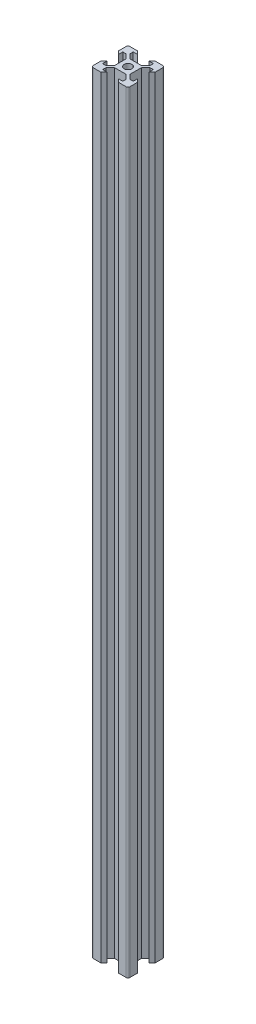
SolidWorks part; units mm, degrees
material "1060 Alloy"
ref_plane "Front Plane" through (0, 0, 0) normal (0, 0, 1) x (1, 0, 0)
ref_plane "Top Plane" through (0, 0, 0) normal (0, 1, 0) x (1, 0, 0)
ref_plane "Right Plane" through (0, 0, 0) normal (1, 0, 0) x (0, 0, -1)
ref_plane "End Plane" through (0, 420, 0) normal (0, 1, 0) x (1, 0, 0)
sketch "MasterLayoutSketch" plane through (0, 0, 0) normal (0, 1, 0) x (1, 0, 0)
  line L0 (-8.325, 3.1) -> (-8.325, 5.5)
  line L1 (-10, -10) -> (10, -10) construction
  line L2 (-10, -10) -> (-10, 10) construction
  line L3 (-10, 10) -> (10, 10) construction
  line L4 (10, -10) -> (10, 10) construction
  line L5 (-10, -10) -> (10, 10) construction
  line L6 (-10, 10) -> (10, -10) construction
  line L7 (-4.775, 10) -> (-3.1, 8.325)
  line L10 (-8.325, 5.5) -> (-6.5607, 5.5)
  line L11 (-10, 4.775) -> (-8.325, 3.1)
  line L12 (-5.5, 8.325) -> (-5.5, 6.5607)
  line L13 (-3.1, 8.325) -> (-5.5, 8.325)
  line L14 (-10, 10) -> (-10, 4.775)
  line L19 (3.1, 8.325) -> (5.5, 8.325)
  line L20 (10, 4.775) -> (8.325, 3.1)
  line L21 (-10, 10) -> (-4.775, 10)
  line L22 (-6.5607, 5.5) -> (-4.1607, 3.1)
  line L23 (-5.5, 6.5607) -> (-3.1, 4.1607)
  line L24 (5.5, 8.325) -> (5.5, 6.5607)
  line L25 (4.775, 10) -> (3.1, 8.325)
  line L26 (8.325, 5.5) -> (6.5607, 5.5)
  line L27 (8.325, 3.1) -> (8.325, 5.5)
  line L28 (10, 10) -> (4.775, 10)
  line L29 (10, 10) -> (10, 4.775)
  line L30 (5.5, 6.5607) -> (3.1, 4.1607)
  line L31 (6.5607, 5.5) -> (4.1607, 3.1)
  line L32 (8.325, -3.1) -> (8.325, -5.5)
  line L33 (4.775, -10) -> (3.1, -8.325)
  line L34 (8.325, -5.5) -> (6.5607, -5.5)
  line L35 (10, -4.775) -> (8.325, -3.1)
  line L36 (5.5, -8.325) -> (5.5, -6.5607)
  line L37 (3.1, -8.325) -> (5.5, -8.325)
  line L38 (10, -10) -> (10, -4.775)
  line L39 (10, -10) -> (4.775, -10)
  line L40 (6.5607, -5.5) -> (4.1607, -3.1)
  line L41 (5.5, -6.5607) -> (3.1, -4.1607)
  line L42 (-3.1, -8.325) -> (-5.5, -8.325)
  line L43 (-10, -4.775) -> (-8.325, -3.1)
  line L44 (-5.5, -8.325) -> (-5.5, -6.5607)
  line L45 (-4.775, -10) -> (-3.1, -8.325)
  line L46 (-8.325, -5.5) -> (-6.5607, -5.5)
  line L47 (-8.325, -3.1) -> (-8.325, -5.5)
  line L48 (-10, -10) -> (-4.775, -10)
  line L49 (-10, -10) -> (-10, -4.775)
  line L50 (-5.5, -6.5607) -> (-3.1, -4.1607)
  line L51 (-6.5607, -5.5) -> (-4.1607, -3.1)
  line L52 (-4.1607, 3.1) -> (-4.1607, -3.1)
  line L53 (-3.1, -4.1607) -> (3.1, -4.1607)
  line L54 (4.1607, -3.1) -> (4.1607, 3.1)
  line L55 (-3.1, 4.1607) -> (3.1, 4.1607)
  circle A0 centre (0, 0) radius 2.1
  point P0 (0, 0)
  point P9 (0, 0)
  dimension "D6" = 4.2
  dimension "D1" = 20
  dimension "D2" = 4
  dimension "D3" = 11
  dimension "D4" = 9.55
  dimension "D5" = 6.2
  dimension "D7" = 1.5
extrude "Main Extrusion" add sketch "MasterLayoutSketch" along normal up to surface (420 mm away) up to plane "End Plane"
fillet "Edge Fillets" radius 1 4 edges at (10, 210, -10) (10, 210, 10) (-10, 210, 10) (-10, 210, -10)
